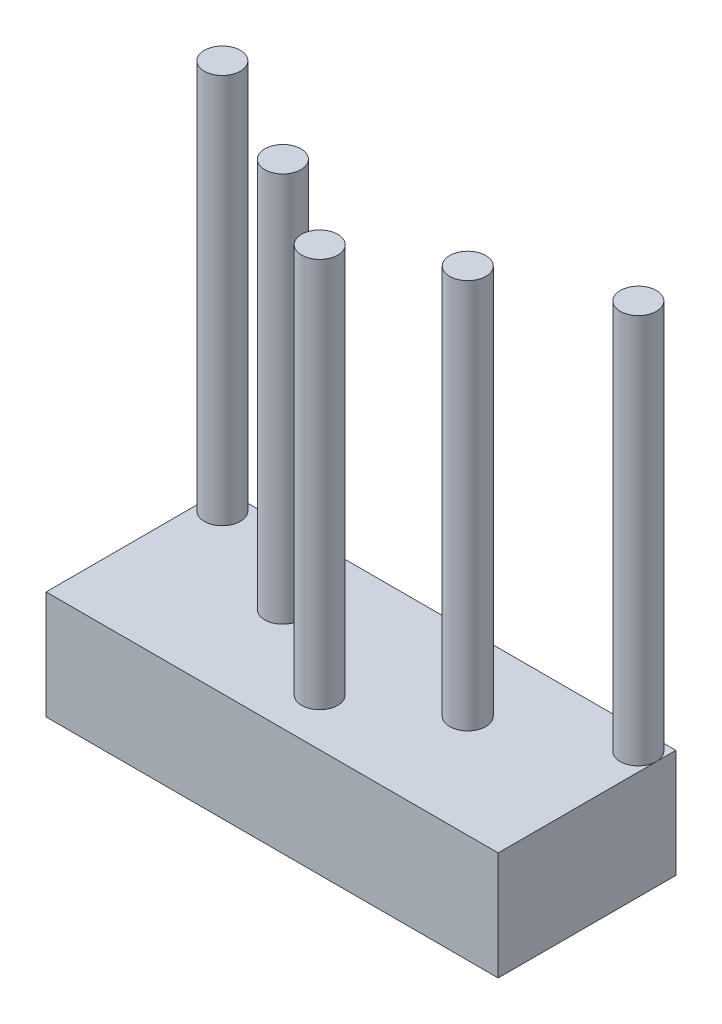
SolidWorks part; units mm, degrees
ref_plane "Front Plane" through (0, 0, 0) normal (0, 0, 1) x (1, 0, 0)
ref_plane "Top Plane" through (0, 0, 0) normal (0, 1, 0) x (1, 0, 0)
ref_plane "Right Plane" through (0, 0, 0) normal (1, 0, 0) x (0, 0, -1)
sketch "Sketch1" plane through (0, 0, 0) normal (0, 1, 0) x (1, 0, 0)
  line L1 (-39.751, 15.621) -> (39.751, 15.621)
  line L2 (-39.751, 15.621) -> (-39.751, -15.621)
  line L3 (-39.751, -15.621) -> (39.751, -15.621)
  line L4 (39.751, 15.621) -> (39.751, -15.621)
  dimension "D1" = 31.242
  dimension "D2" = 79.502
  dimension "D3" = 39.751
  dimension "D4" = 15.621
extrude "Boss-Extrude1" add sketch "Sketch1" along normal blind 19.05
sketch "Sketch2" plane through (0, 19.05, 0) normal (0, 1, 0) x (1, 0, 0)
  line L0 (-36.576, 12.192) -> (-39.751, 12.192) construction
  line L1 (-16.256, 2.5151) -> (-19.431, 2.5151) construction
  line L2 (0, -7.2639) -> (-3.175, -7.2639) construction
  line L3 (16.256, 2.5151) -> (13.081, 2.5151) construction
  line L4 (36.576, 12.192) -> (33.401, 12.192) construction
  line L5 (-36.576, 12.192) -> (-33.401, 12.192) construction
  line L6 (-16.256, 2.5151) -> (-13.081, 2.5151) construction
  line L7 (16.256, 2.5151) -> (19.431, 2.5151) construction
  line L8 (0, -7.2639) -> (3.175, -7.2639) construction
  line L9 (36.576, 12.192) -> (39.751, 12.192) construction
  circle A0 centre (-36.576, 12.192) radius 3.175
  circle A4 centre (-16.256, 2.5151) radius 3.175
  circle A5 centre (0, -7.2639) radius 3.175
  circle A6 centre (16.256, 2.5151) radius 3.175
  circle A7 centre (36.576, 12.192) radius 3.175
  dimension "D1" = 79.502
  dimension "D5" = 0
  dimension "D10" = 20.32
  dimension "D11" = 16.256
  dimension "D2" = 0
  dimension "D3" = 12.192
  dimension "D4" = 39.751
  dimension "D6" = 19.4559
  dimension "D7" = 9.779
  dimension "D8" = 0
  dimension "D9" = 20.32
extrude "Boss-Extrude2" add sketch "Sketch2" along normal blind 68.58
equation "\"0..8in\"=0.625491"
